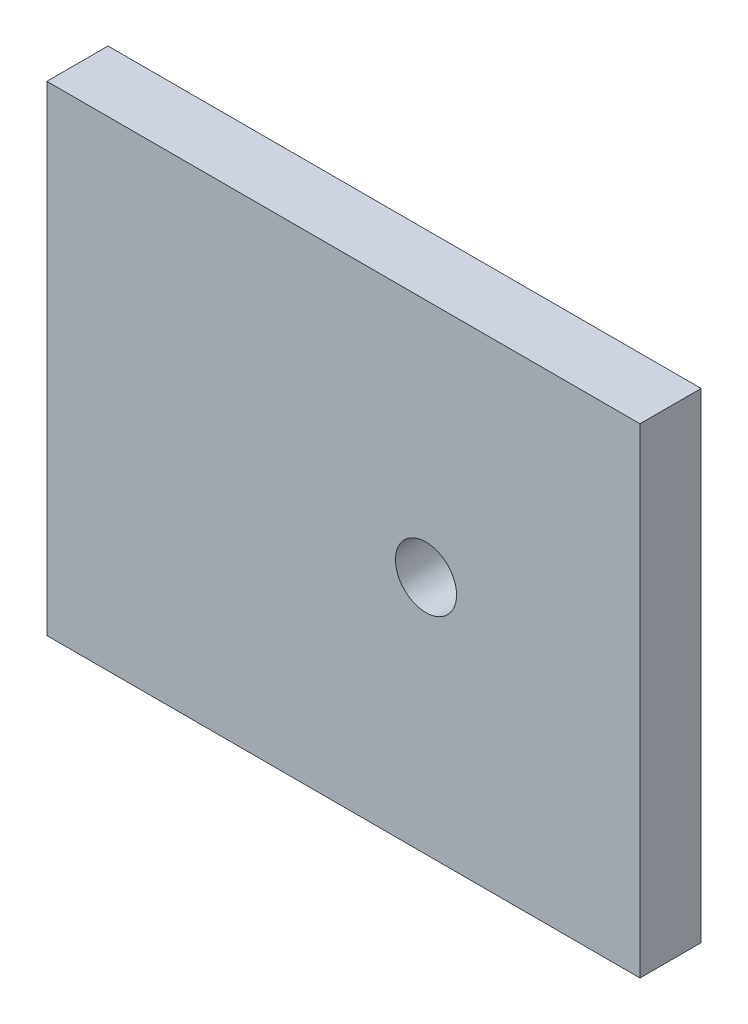
SolidWorks part; units mm, degrees
ref_plane "Front Plane" through (0, 0, 0) normal (0, 0, 1) x (1, 0, 0)
ref_plane "Top Plane" through (0, 0, 0) normal (0, 1, 0) x (1, 0, 0)
ref_plane "Right Plane" through (0, 0, 0) normal (1, 0, 0) x (0, 0, -1)
sketch "Sketch1" plane through (0, 0, 0) normal (0, 0, 1) x (1, 0, 0)
  line L1 (-48.5, -39.25) -> (48.5, -39.25)
  line L2 (-48.5, -39.25) -> (-48.5, 39.25)
  line L3 (-48.5, 39.25) -> (48.5, 39.25)
  line L4 (48.5, -39.25) -> (48.5, 39.25)
  line L5 (-48.5, -39.25) -> (48.5, 39.25) construction
  line L6 (-48.5, 39.25) -> (48.5, -39.25) construction
  point P0 (0, 0)
  dimension "D1" = 97
  dimension "D2" = 78.5
extrude "Boss-Extrude1" add sketch "Sketch1" along normal blind 10
sketch "Sketch2" plane through (0, 0, 10) normal (0, 0, 1) x (1, 0, 0)
  line L2 (48.5, -39.25) -> (48.5, 39.25) construction
  line L3 (-24.7721, 0) -> (48.5, 0) construction
  circle A1 centre (13.5, 0) radius 5
  dimension "D1" = 10
  dimension "D2" = 35
extrude "Cut-Extrude1" cut sketch "Sketch2" against normal up to next
sketch "Sketch3" plane through (0, 0, 0) normal (0, 0, -1) x (-1, 0, 0)
  line L0 (0, 0) -> (48.5, 0) construction
  line L1 (48.5, 39.25) -> (48.5, -39.25) construction
  circle A0 centre (24.25, 0) radius 11
  dimension "D1" = 22
extrude "Cut-Extrude2" cut sketch "Sketch3" against normal blind 5
